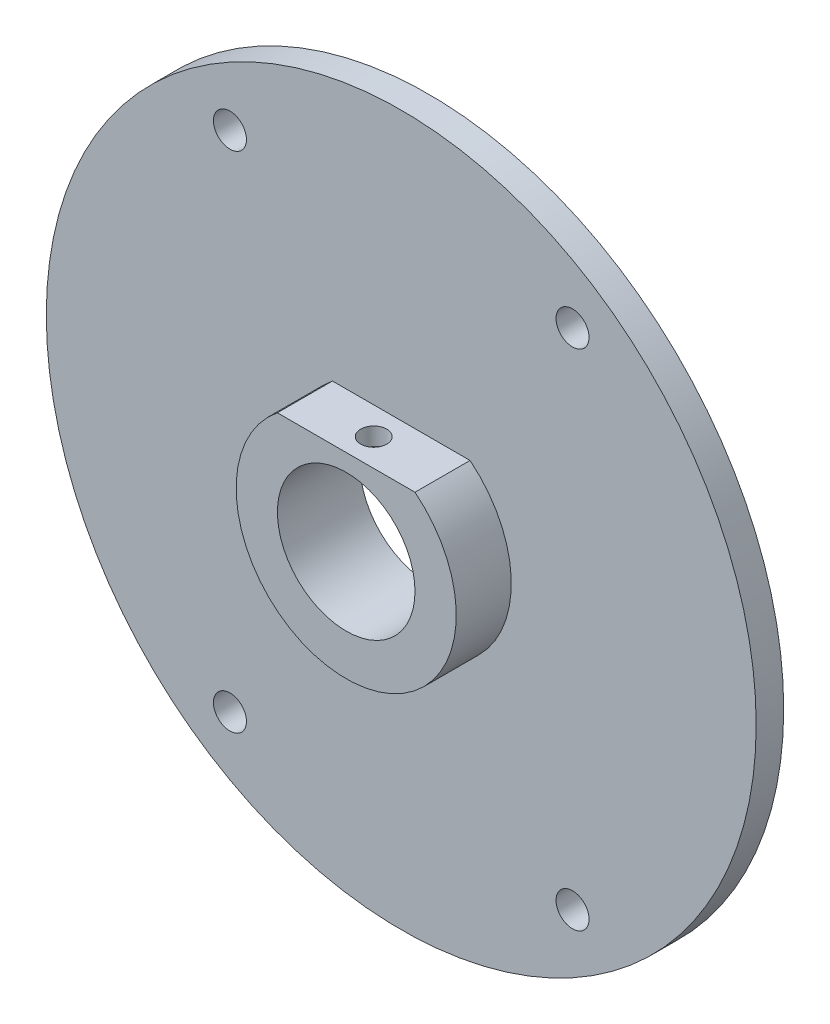
SolidWorks part; units mm, degrees
ref_plane "前视基准面" through (0, 0, 0) normal (0, 0, 1) x (1, 0, 0)
ref_plane "上视基准面" through (0, 0, 0) normal (0, 1, 0) x (1, 0, 0)
ref_plane "右视基准面" through (0, 0, 0) normal (1, 0, 0) x (0, 0, -1)
other "Configuration Table"
sketch "草图1" plane through (0, 0, 0) normal (0, 0, 1) x (1, 0, 0)
  line L0 (53, 92.55) -> (42, 92.55) construction
  line L1 (53, 92.55) -> (42, 92.55)
  line L7 (48.7989, 18.313) -> (50.7876, 13.9195)
  line L8 (50.7876, 13.9195) -> (54.3, 13.9195)
  line L9 (54.3, 13.9195) -> (54.3, 21.7336)
  line L10 (60, 23.4615) -> (60, 25.488)
  line L11 (73.7, 21.7336) -> (73.7, 14.6774)
  line L12 (73.7, 14.6774) -> (76.8998, 13.229)
  line L13 (76.8998, 13.229) -> (79.2011, 18.313)
  line L14 (79.2011, -18.313) -> (74.1124, -7.071)
  line L15 (74.1124, -7.071) -> (73.7, -6.9156)
  line L16 (73.7, -6.9156) -> (73.7, -21.7336)
  line L17 (54.3, -21.7336) -> (54.3, -7.16)
  line L18 (54.3, -7.16) -> (53.9884, -6.8484)
  line L19 (53.9884, -6.8484) -> (48.7989, -18.313)
  line L20 (48.7989, -18.313) -> (47.2608, -19.6326)
  line L21 (68, 25.488) -> (68, 23.4615)
  line L22 (73.7, 21.7336) -> (73.7, 14.6774)
  line L23 (73.7, 14.6774) -> (76.8998, 13.229)
  line L24 (76.8998, 13.229) -> (79.2011, 18.313)
  line L25 (79.2011, -18.313) -> (74.1124, -7.071)
  line L26 (74.1124, -7.071) -> (73.7, -6.9156)
  line L27 (73.7, -6.9156) -> (73.7, -21.7336)
  line L28 (54.3, -21.7336) -> (54.3, -7.16)
  line L29 (54.3, -7.16) -> (53.9884, -6.8484)
  line L30 (53.9884, -6.8484) -> (48.7989, -18.313)
  line L31 (48.7989, -18.313) -> (47.2608, -19.6326)
  line L32 (68, 25.488) -> (68, 23.4615)
  line L33 (42.0515, -13.5611) -> (43.5896, -12.2415)
  line L34 (48.7989, 18.313) -> (50.7876, 13.9195)
  line L35 (50.7876, 13.9195) -> (54.3, 13.9195)
  line L36 (54.3, 13.9195) -> (54.3, 21.7336)
  line L37 (60, 23.4615) -> (60, 25.488)
  line L38 (42.0515, -13.5611) -> (43.5896, -12.2415)
  circle A0 centre (76.4506, 18.313) radius 1.2 construction
  circle A1 centre (76.4506, 18.313) radius 1.2
  circle A2 centre (51.5494, 18.313) radius 1.2 construction
  arc A3 (60, 23.4615) -> (54.3, 21.7336) centre (64, 0) ccw
  arc A4 (79.2011, -18.313) -> (79.2011, 18.313) centre (64, 0) ccw
  arc A5 (54.3, -21.7336) -> (73.7, -21.7336) centre (64, 0) ccw
  arc A6 (47.2608, -19.6326) -> (68, 25.488) centre (64, 0) ccw
  arc A7 (73.7, 21.7336) -> (68, 23.4615) centre (64, 0) ccw
  arc A8 (79.2011, -18.313) -> (79.2011, 18.313) centre (64, 0) ccw
  arc A9 (54.3, -21.7336) -> (73.7, -21.7336) centre (64, 0) ccw
  arc A10 (47.2608, -19.6326) -> (68, 25.488) centre (64, 0) ccw
  arc A11 (73.7, 21.7336) -> (68, 23.4615) centre (64, 0) ccw
  arc A12 (60, 25.488) -> (42.0515, -13.5611) centre (64, 0) ccw
  arc A13 (48.7989, 18.313) -> (43.5896, -12.2415) centre (64, 0) ccw
  arc A14 (60, 23.4615) -> (54.3, 21.7336) centre (64, 0) ccw
  arc A15 (60, 25.488) -> (42.0515, -13.5611) centre (64, 0) ccw
  arc A16 (48.7989, 18.313) -> (43.5896, -12.2415) centre (64, 0) ccw
  circle A17 centre (51.5494, 18.313) radius 1.2
  circle A18 centre (51.5494, -18.313) radius 1.2 construction
  circle A19 centre (51.5494, -18.313) radius 1.2
  circle A20 centre (76.4506, -18.313) radius 1.2 construction
  circle A21 centre (76.4506, -18.313) radius 1.2
  circle A22 centre (64, 0) radius 5 construction
  circle A23 centre (64, 0) radius 5
  circle A24 centre (64, 0) radius 23.8
  circle A25 centre (64, 0) radius 25.8
  dimension "D1" = 0
  dimension "D2" = 0
extrude "凸台-拉伸1" add sketch "草图1" along normal blind 2 contours A11 A24 A14 L36 L35 L34 A16 L30 L29 L28 A9 L27 L26 L25 A8 L24 L23 L22 A23 | A24 A14 L37 A15 L38 A16 | A24 A8 A9 L31 A10 L32 A11 | L32 A25 L37 A24 | L38 A25 L31 A24 | L30 A24 L28 L29 A19 | L27 A24 L25 L26 A21 | L24 A24 L22 L23 A1 | L36 A24 L34 L35 A17
sketch "草图2" plane through (0, 0, 2) normal (0, 0, 1) x (1, 0, 0)
  line L0 (69, 6.245) -> (59, 6.245)
  circle A0 centre (64, 0) radius 5 construction
  circle A1 centre (64, 0) radius 25.8
  circle A2 centre (64, 0) radius 25.8
  circle A3 centre (64, 0) radius 5
  circle A4 centre (64, 0) radius 8
  circle M5 centre (64, 0) radius 5
  dimension "D3" = 10
  dimension "D1" = 0
  dimension "D2" = 3
extrude "凸台-拉伸2" add sketch "草图2" along normal blind 4 contours L0 A4 M5
sketch "草图3" plane through (0, 6.245, 0) normal (0, 1, 0) x (1, 0, 0)
  line L0 (69, -2) -> (59, -6)
  line L4 (69, -2) -> (59, -2)
  line L5 (59, -2) -> (59, -6)
  line L6 (59, -6) -> (69, -6)
  line L7 (69, -6) -> (69, -2)
  line L8 (69, -2) -> (59, -2)
  line L9 (59, -2) -> (59, -6)
  line L10 (59, -6) -> (69, -6)
  line L11 (69, -6) -> (69, -2)
  circle A0 centre (64, -4) radius 0.95
  dimension "D2" = 1.9
  dimension "D1" = 0
extrude "切除-拉伸1" cut sketch "草图3" against normal blind 4 contours L0 A0 | L0 A0
